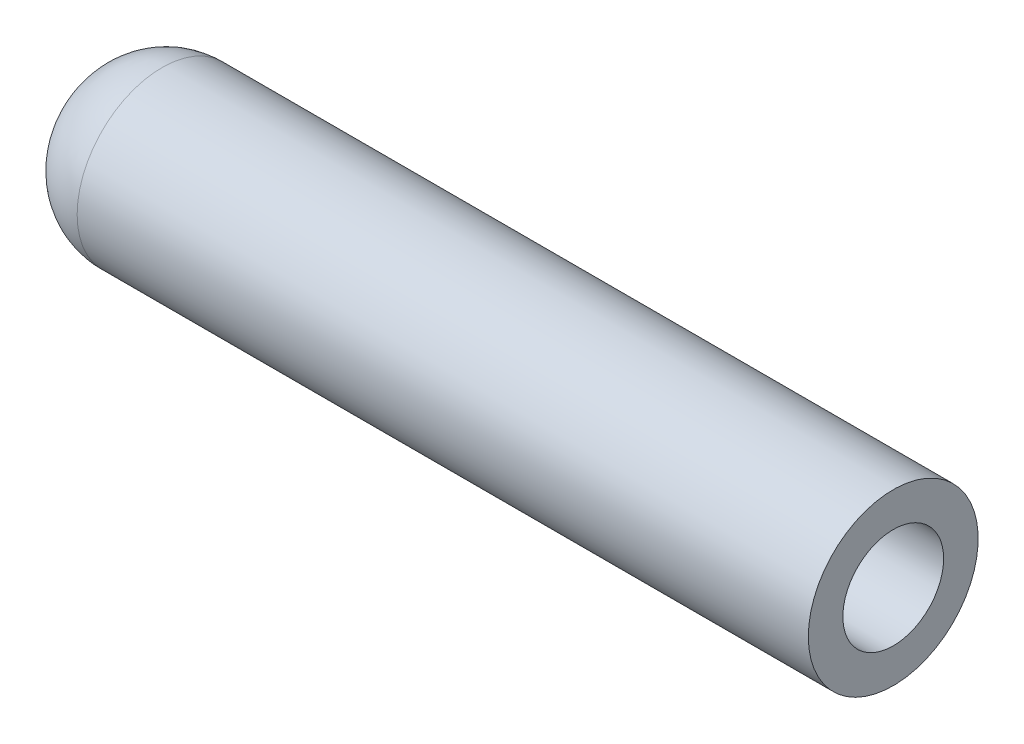
SolidWorks part; units mm, degrees
ref_plane "Front Plane" through (0, 0, 0) normal (0, 0, 1) x (1, 0, 0)
ref_plane "Top Plane" through (0, 0, 0) normal (0, 1, 0) x (1, 0, 0)
ref_plane "Right Plane" through (0, 0, 0) normal (1, 0, 0) x (0, 0, -1)
sketch "Sketch2" plane through (0, 0, 0) normal (0, 0, 1) x (1, 0, 0)
  line L0 (0, 7.5) -> (72.5576, 7.5)
  line L1 (72.5576, -0.9281) -> (72.5576, 7.5)
  line L2 (-7.4424, -0.9281) -> (72.5576, -0.9281)
  arc A0 (0, 7.5) -> (-7.4424, -0.9281) centre (0, 0) ccw
  dimension "D1" = 15
  dimension "D2" = 80
revolve "Revolve3" add sketch "Sketch2" angle 360 about L2
sketch "Sketch3" plane through (72.5576, 0, 0) normal (1, 0, 0) x (0, 0, -1)
  circle A0 centre (0, -0.9281) radius 5
  circle A1 centre (0, -0.9281) radius 8.4281 construction
  dimension "D1" = 10
extrude "Cut-Extrude1" cut sketch "Sketch3" against normal blind 50
